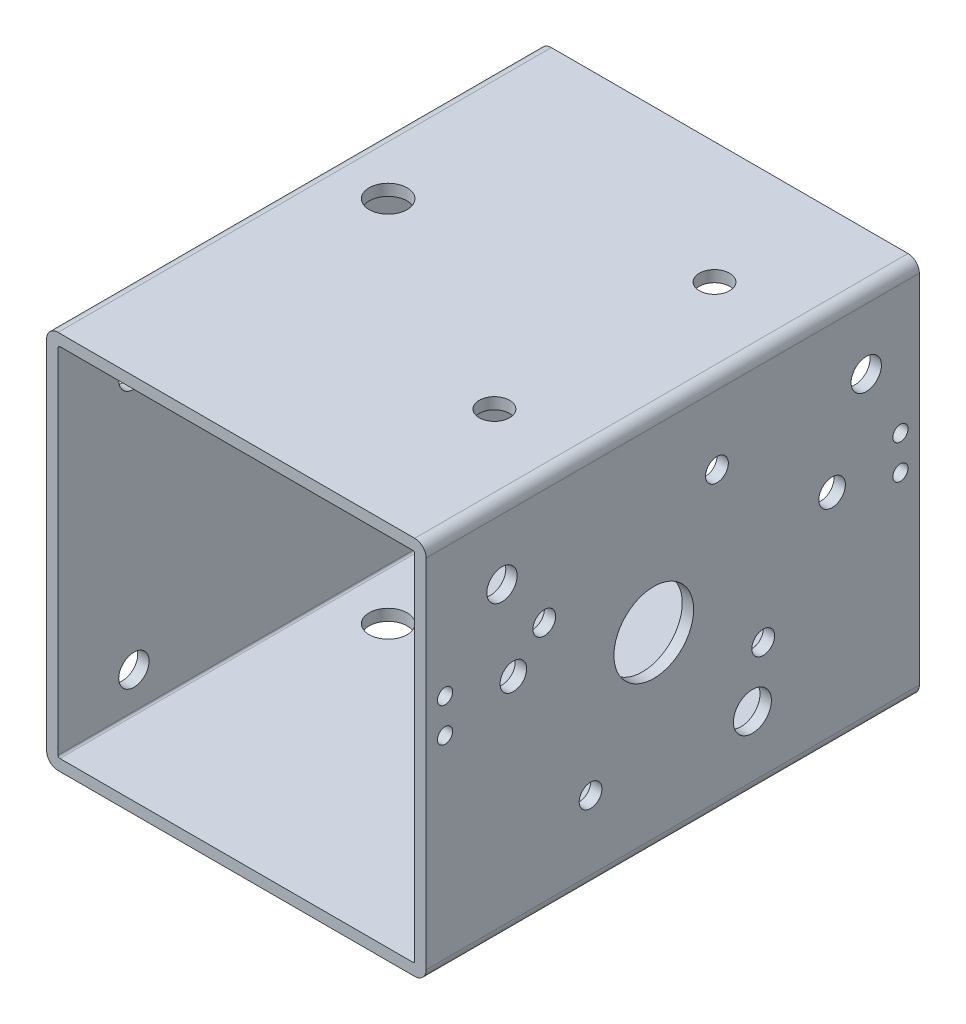
SolidWorks part; units mm, degrees
ref_plane "Front Plane" through (0, 0, 0) normal (0, 0, 1) x (1, 0, 0)
ref_plane "Top Plane" through (0, 0, 0) normal (0, 1, 0) x (1, 0, 0)
ref_plane "Right Plane" through (0, 0, 0) normal (1, 0, 0) x (0, 0, -1)
sketch "Sketch1" plane through (0, 0, 0) normal (0, 0, 1) x (1, 0, 0)
  line L1 (-50, 50) -> (50, 50)
  line L2 (-50, 50) -> (-50, -50)
  line L3 (-50, -50) -> (50, -50)
  line L4 (50, 50) -> (50, -50)
  line L5 (-50, 50) -> (50, -50) construction
  line L6 (-50, -50) -> (50, 50) construction
  point P0 (0, 0)
  dimension "D1" = 100
  dimension "D2" = 100
extrude "Extrude-Thin1" add sketch "Sketch1" along normal blind 130 thin
fillet "Fillet1" radius 0.5 4 edges at (-47, -47, 65) (-47, 47, 65) (47, 47, 65) (47, -47, 65)
fillet "Fillet2" radius 3 4 edges at (50, -50, 65) (-50, -50, 65) (50, 50, 65) (-50, 50, 65)
sketch "Holes - top" plane through (0, 0, 0) normal (0, 1, 0) x (1, 0, 0)
  line L0 (-3, 0) -> (-3, -130) construction
  line L1 (47, -130) -> (-47, -130) construction
  line L2 (-23, 0) -> (-23, -130) construction
  line L3 (47, 0) -> (-47, 0) construction
  line L4 (17, 0) -> (17, -130) construction
  circle A0 centre (-34, -56) radius 11 construction
  circle A1 centre (28, -90) radius 11 construction
  circle A2 centre (28, -32) radius 11 construction
  dimension "D4" = 22
  dimension "D1" = 40
  dimension "D2" = 40
  dimension "D3" = 32
  dimension "D5" = 56
  dimension "D6" = 3
hole_wizard "Ø8.0 (8) Diameter Hole2" positions "Sketch6" profile "Sketch5" hole size "Ø8.0" standard "ANSI Metric" end condition through all
sketch "Sketch6" plane through (0, 50, 0) normal (0, 1, 0) x (1, 0, 0)
  point P0 (28, -32)
  point P6 (28, -90)
sketch "Sketch5" plane through (28, 50, 32) normal (1, 0, 0) x (0, 0, 1)
  line L0 (0, 0) -> (0, 100)
  line L1 (0, 100) -> (4, 100)
  line L2 (4, 100) -> (4, 0)
  line L5 (4, 0) -> (0, 0)
  line L11 (0, -6.35) -> (0, 107.95) construction
  dimension "Thru Hole Dia." = 8
  dimension "Thru Hole Depth" = 100
sketch "Holes - side" plane through (0, 0, 0) normal (1, 0, 0) x (0, 0, -1)
  line L0 (0, 0) -> (-130, 0) construction
  line L1 (-130, -47) -> (-130, 47) construction
  line L2 (-130, 20) -> (0, 20) construction
  line L3 (0, -47) -> (0, 47) construction
  line L4 (-130, -20) -> (0, -20) construction
  circle A0 centre (-110, 31) radius 11 construction
  circle A1 centre (-14, 31) radius 11 construction
  circle A2 centre (-44, -31) radius 11 construction
  dimension "D1" = 40
  dimension "D2" = 22
  dimension "D3" = 20
  dimension "D4" = 14
  dimension "D5" = 44
hole_wizard "Ø8.0 (8) Diameter Hole3" positions "Sketch9" profile "Sketch8" hole size "Ø8.0" standard "ANSI Metric" end condition through all
sketch "Sketch9" plane through (50, 0, 0) normal (1, 0, 0) x (0, 0, -1)
  point P0 (-14, 31)
  point P3 (-110, 31)
sketch "Sketch8" plane through (50, 31, 14) normal (0, 1, 0) x (0, 0, -1)
  line L0 (0, 0) -> (0, 100)
  line L1 (0, 100) -> (4, 100)
  line L2 (4, 100) -> (4, 0)
  line L5 (4, 0) -> (0, 0)
  line L11 (0, -6.35) -> (0, 107.95) construction
  dimension "Thru Hole Dia." = 8
  dimension "Thru Hole Depth" = 100
hole_wizard "Ø10.0 (10) Diameter Hole1" positions "Sketch12" profile "Sketch11" hole size "Ø10.0" standard "ANSI Metric" end condition through all
sketch "Sketch12" plane through (0, 50, 0) normal (0, 1, 0) x (1, 0, 0)
  point P0 (-34, -56)
sketch "Sketch11" plane through (-34, 50, 56) normal (1, 0, 0) x (0, 0, 1)
  line L0 (0, 0) -> (0, 100)
  line L1 (0, 100) -> (5, 100)
  line L2 (5, 100) -> (5, 0)
  line L5 (5, 0) -> (0, 0)
  line L11 (0, -6.35) -> (0, 107.95) construction
  dimension "Thru Hole Dia." = 10
  dimension "Thru Hole Depth" = 100
hole_wizard "Ø10.0 (10) Diameter Hole2" positions "Sketch14" profile "Sketch13" hole size "Ø10.0" standard "ANSI Metric" end condition through all
sketch "Sketch14" plane through (50, 0, 0) normal (1, 0, 0) x (0, 0, -1)
  point P0 (-44, -31)
sketch "Sketch13" plane through (50, -31, 44) normal (0, 1, 0) x (0, 0, -1)
  line L0 (0, 0) -> (0, 100)
  line L1 (0, 100) -> (5, 100)
  line L2 (5, 100) -> (5, 0)
  line L5 (5, 0) -> (0, 0)
  line L11 (0, -6.35) -> (0, 107.95) construction
  dimension "Thru Hole Dia." = 10
  dimension "Thru Hole Depth" = 100
hole_wizard "M8x1.25 Tapped Hole1" positions "Sketch18" profile "Sketch17" tap size "M8x1.25" standard "ANSI Metric"
sketch "Sketch18" plane through (-50, 0, 0) normal (-1, 0, 0) x (0, 0, 1)
  line L0 (56, 35) -> (56, -15) construction
  point P0 (56, -15)
  point P2 (56, 35)
  dimension "D1" = 56
  dimension "D2" = 35
  dimension "D3" = 15
sketch "Sketch17" plane through (-50, -15, 56) normal (0, 1, 0) x (0, 0, 1)
  line L0 (0, 0) -> (0, 3)
  line L1 (0, 3) -> (3.4, 3)
  line L2 (3.4, 3) -> (3.4, 0)
  line L5 (3.4, 0) -> (0, 0)
  line L11 (0, -6.35) -> (0, 107.95) construction
  dimension "Thru Tap Drill Dia." = 6.8
  dimension "Thru Tap Drill Depth" = 3
cosmetic thread "Hole Thread1" parameters "D2"=8
cosmetic thread "Hole Thread2" parameters "D2"=8
hole_wizard "M8x1.25 Tapped Hole2" positions "Sketch21" profile "Sketch20" tap size "M8x1.25" standard "ANSI Metric"
sketch "Sketch21" plane through (0, -50, 0) normal (0, -1, 0) x (-1, 0, 0)
  line L0 (20, -44) -> (-35, -44) construction
  point P0 (20, -44)
  point P2 (-35, -44)
  dimension "D1" = 44
  dimension "D2" = 35
  dimension "D3" = 20
sketch "Sketch20" plane through (-20, -50, 44) normal (1, 0, 0) x (0, 0, -1)
  line L0 (0, 0) -> (0, 3)
  line L1 (0, 3) -> (3.4, 3)
  line L2 (3.4, 3) -> (3.4, 0)
  line L5 (3.4, 0) -> (0, 0)
  line L11 (0, -6.35) -> (0, 107.95) construction
  dimension "Thru Tap Drill Dia." = 6.8
  dimension "Thru Tap Drill Depth" = 3
cosmetic thread "Hole Thread3" parameters "D2"=8
cosmetic thread "Hole Thread4" parameters "D2"=8
sketch "Holes - Nema 23 motor" plane through (0, 0, 0) normal (1, 0, 0) x (0, 0, -1)
  line L0 (-98.8427, 16.6524) -> (-53.3476, 28.8427) construction
  line L1 (-98.8427, 16.6524) -> (-86.6524, -28.8427) construction
  line L2 (-53.3476, 28.8427) -> (-41.1573, -16.6524) construction
  line L3 (-86.6524, -28.8427) -> (-41.1573, -16.6524) construction
  line L4 (-98.8427, 16.6524) -> (-41.1573, -16.6524) construction
  line L5 (-53.3476, 28.8427) -> (-86.6524, -28.8427) construction
  line L6 (0, 0) -> (-130, 0) construction
  point P1 (-70, 0)
  dimension "D1" = 70
  dimension "D2" = 47.1
  dimension "D3" = 47.1
  dimension "D4" = 15
hole_wizard "Ø21.0 (21) Diameter Hole1" positions "Sketch24" profile "Sketch23" hole size "Ø21.0" standard "ANSI Metric"
sketch "Sketch24" plane through (50, 0, 0) normal (1, 0, 0) x (0, 0, -1)
  point P0 (-70, 0)
sketch "Sketch23" plane through (50, 0, 70) normal (0, 1, 0) x (0, 0, -1)
  line L0 (0, 0) -> (0, 3)
  line L1 (0, 3) -> (10.5, 3)
  line L2 (10.5, 3) -> (10.5, 0)
  line L5 (10.5, 0) -> (0, 0)
  line L11 (0, -6.35) -> (0, 107.95) construction
  dimension "Thru Hole Dia." = 21
  dimension "Thru Hole Depth" = 3
hole_wizard "Ø6.0 (6) Diameter Hole1" positions "Sketch26" profile "Sketch25" hole size "Ø6.0" standard "ANSI Metric"
sketch "Sketch26" plane through (50, 0, 0) normal (1, 0, 0) x (0, 0, -1)
  point P0 (-41.1573, -16.6524)
  point P3 (-53.3476, 28.8427)
  point P6 (-98.8427, 16.6524)
  point P9 (-86.6524, -28.8427)
sketch "Sketch25" plane through (50, -16.6524, 41.1573) normal (0, 1, 0) x (0, 0, -1)
  line L0 (0, 0) -> (0, 3)
  line L1 (0, 3) -> (3, 3)
  line L2 (3, 3) -> (3, 0)
  line L5 (3, 0) -> (0, 0)
  line L11 (0, -6.35) -> (0, 107.95) construction
  dimension "Thru Hole Dia." = 6
  dimension "Thru Hole Depth" = 3
sketch "Sketch27" plane through (50, 0, 0) normal (1, 0, 0) x (0, 0, -1)
  line L1 (0, -47) -> (0, 47) construction
  line L2 (-130, 50) -> (0, 50) construction
  line L3 (-65, 66.9997) -> (-65, -40.3101) construction
  line L4 (-130, -47) -> (-130, 47) construction
  circle A0 centre (-5, 13) radius 2
  circle A1 centre (-5, 4) radius 2
  circle A2 centre (-23, 8.5) radius 3.5
  circle A3 centre (-107, 8.5) radius 3.5
  circle A4 centre (-125, 4) radius 2
  circle A5 centre (-125, 13) radius 2
  dimension "D1" = 4
  dimension "D2" = 9
  dimension "D3" = 5
  dimension "D4" = 46
  dimension "D7" = 18
  dimension "D8" = 4.5
  dimension "D9" = 7
  dimension "D5" = 0
  dimension "D6" = 65
extrude "Cut-Extrude1" cut sketch "Sketch27" against normal up to next
sketch "Sketch31" plane through (-50, 0, 0) normal (-1, 0, 0) x (0, 0, 1)
  line L0 (0, 47) -> (0, -47) construction
  line L1 (130, 47) -> (130, -47) construction
  line L2 (0, -47) -> (130, -47) construction
  circle A0 centre (14, -37) radius 4
  circle A1 centre (110, -37) radius 4
  dimension "D1" = 8
  dimension "D2" = 8
  dimension "D3" = 14
  dimension "D4" = 20
  dimension "D5" = 10
extrude "Cut-Extrude2" cut sketch "Sketch31" against normal up to next
equation "\"a\"= \"Trolley Profile@Plasma Beta.Assembly\""
equation "\"b\"= \"Trolley Profile Thickness@Plasma Beta.Assembly\""
equation "\"L\"= 130"
equation "\"D2@Sketch1\"=\"a\""
equation "\"D1@Sketch1\"=\"a\""
equation "\"D1@Extrude-Thin1\"=\"L\""
equation "\"D5@Extrude-Thin1\"=\"b\""
equation "\"D1@Fillet2\"=\"b\""
equation "\"d-bearing\"= 22'diameter of bearing"
equation "\"a-small\"= \"Beam Profile@Plasma Beta.Assembly\"'profile of smaller beam"
equation "\"D4@Holes - top\"=\"d-bearing\""
equation "\"D2@Holes - side\"=\"d-bearing\""
equation "\"D1@Holes - top\"=\"a-small\""
equation "\"D1@Holes - side\"=\"a-small\""
